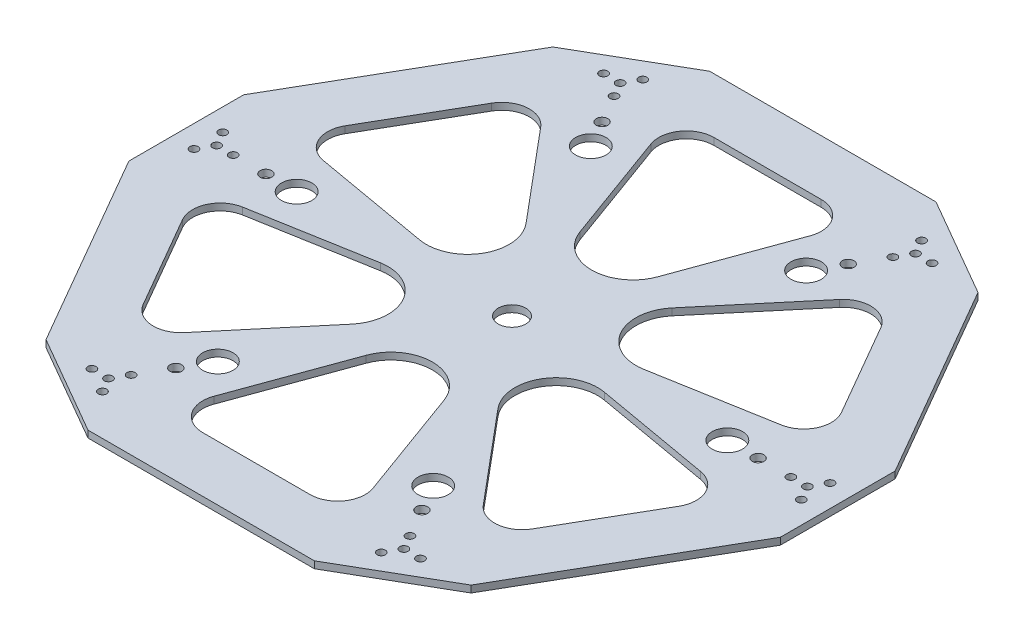
SolidWorks part; units mm, degrees
ref_plane "前视基准面" through (0, 0, 0) normal (0, 0, 1) x (1, 0, 0)
ref_plane "上视基准面" through (0, 0, 0) normal (0, 1, 0) x (1, 0, 0)
ref_plane "右视基准面" through (0, 0, 0) normal (1, 0, 0) x (0, 0, -1)
other "Configuration Table"
sketch "草图2" plane through (0, 0, 0) normal (0, 1, 0) x (1, 0, 0)
  line L1 (45, 0) -> (22.5, 38.9711)
  line L2 (22.5, 38.9711) -> (-22.5, 38.9711)
  line L3 (-22.5, 38.9711) -> (-45, 0)
  line L4 (-45, 0) -> (-22.5, -38.9711)
  line L5 (-22.5, -38.9711) -> (22.5, -38.9711)
  line L6 (22.5, -38.9711) -> (45, 0)
  line L7 (-54.5, 0) -> (-27.25, -47.1984)
  line L8 (-27.25, -47.1984) -> (27.25, -47.1984)
  line L9 (27.25, -47.1984) -> (54.5, 0)
  line L10 (54.5, 0) -> (27.25, 47.1984)
  line L11 (27.25, 47.1984) -> (-27.25, 47.1984)
  line L12 (-27.25, 47.1984) -> (-54.5, 0)
  circle A0 centre (0, 0) radius 38.9711 construction
  circle A1 centre (0, 0) radius 47.1984 construction
  circle A2 centre (0, 0) radius 5
  dimension "D3" = 10
  dimension "D1" = 45
  dimension "D2" = 9.5
extrude "凸台-拉伸1" add sketch "草图2" along normal blind 2.5 contours L5 L6 L1 L2 L3 L4 | L11 L12 L7 L8 L9 L10 L6 L5 L4 L3 L2 L1
sketch "草图3" plane through (0, 2.5, 0) normal (0, 1, 0) x (1, 0, 0)
  line L7 (-45, 0) -> (-22.5, -38.9711) construction
  line L8 (-22.5, -38.9711) -> (22.5, -38.9711) construction
  line L9 (22.5, -38.9711) -> (45, 0) construction
  line L10 (45, 0) -> (22.5, 38.9711) construction
  line L11 (22.5, 38.9711) -> (-22.5, 38.9711) construction
  line L12 (-22.5, 38.9711) -> (-45, 0) construction
  circle A0 centre (0, 0) radius 38.9711 construction
  circle A7 centre (-22.5, 38.9711) radius 2.1
  circle A8 centre (22.5, 38.9711) radius 2.1
  circle A9 centre (45, 0) radius 2.1
  circle A10 centre (22.5, -38.9711) radius 2.1
  circle A11 centre (-22.5, -38.9711) radius 2.1
  circle A12 centre (-45, 0) radius 2.1
  point P23 (0, 0)
  point P24 (0, 0)
  dimension "D2" = 4.2
  dimension "D1" = 45
  dimension "D3" = 6
extrude "切除-拉伸1" [suppressed] cut sketch "草图3" against normal blind 2.5
sketch "草图4" plane through (0, 2.5, 0) normal (0, 1, 0) x (1, 0, 0)
  line L0 (-27.25, 47.1984) -> (-54.5, 0) construction
  line L1 (-54.5, 0) -> (-27.25, -47.1984)
  line L2 (-27.25, -47.1984) -> (27.25, -47.1984)
  line L3 (27.25, -47.1984) -> (54.5, 0)
  line L4 (54.5, 0) -> (27.25, 47.1984)
  line L5 (27.25, 47.1984) -> (-27.25, 47.1984)
  line L6 (-27.25, 47.1984) -> (-54.5, 0)
  line L7 (-100.688, 0) -> (-50.344, -87.1984)
  line L8 (-50.344, -87.1984) -> (50.344, -87.1984)
  line L9 (50.344, -87.1984) -> (100.688, 0)
  line L10 (100.688, 0) -> (50.344, 87.1984)
  line L11 (50.344, 87.1984) -> (-50.344, 87.1984)
  line L12 (-50.344, 87.1984) -> (-100.688, 0)
  circle A0 centre (0, 0) radius 47.1984 construction
  circle A1 centre (0, 0) radius 87.1984 construction
  dimension "D1" = 40
extrude "凸台-拉伸2" add sketch "草图4" against normal up to surface (2.5 mm away) up to face at (0, 0, 5)
sketch "草图5" plane through (0, 2.5, 0) normal (0, 1, 0) x (1, 0, 0)
  line L0 (-50.344, 87.1984) -> (-100.688, 0) construction
  line L1 (-89.141, 0) -> (-44.5705, -77.1984) construction
  line L2 (-44.5705, -77.1984) -> (44.5705, -77.1984) construction
  line L3 (44.5705, -77.1984) -> (89.141, 0) construction
  line L4 (89.141, 0) -> (44.5705, 77.1984) construction
  line L5 (44.5705, 77.1984) -> (-44.5705, 77.1984) construction
  line L6 (-44.5705, 77.1984) -> (-89.141, 0) construction
  circle A0 centre (0, 0) radius 77.1984 construction
  circle A1 centre (-44.5705, 77.1984) radius 2.1
  circle A2 centre (44.5705, 77.1984) radius 2.1
  circle A3 centre (89.141, 0) radius 2.1
  circle A4 centre (44.5705, -77.1984) radius 2.1
  circle A5 centre (-44.5705, -77.1984) radius 2.1
  circle A6 centre (-89.141, 0) radius 2.1
  point P24 (0, 0)
  dimension "D2" = 4.2
  dimension "D1" = 10
  dimension "D3" = 6
extrude "切除-拉伸2" cut sketch "草图5" against normal blind 10
sketch "草图8" plane through (0, 2.5, 0) normal (0, 1, 0) x (1, 0, 0)
  line L0 (50.344, 87.1984) -> (-50.344, 87.1984) construction
  line L1 (-100.688, 0) -> (-50.344, -87.1984) construction
  circle A0 centre (-44.5705, 77.1984) radius 10
  circle A1 centre (44.5705, 77.1984) radius 10
  circle A2 centre (89.141, 0) radius 10
  circle A3 centre (44.5705, -77.1984) radius 10
  circle A4 centre (-44.5705, -77.1984) radius 10
  circle A5 centre (-89.141, 0) radius 10
  circle A6 centre (-113.6008, 65.5875) radius 60
  circle A7 centre (0, 131.175) radius 60
  circle A8 centre (113.6008, 65.5875) radius 60
  circle A9 centre (113.6008, -65.5875) radius 60
  circle A10 centre (0, -131.175) radius 60
  circle A11 centre (-113.6008, -65.5875) radius 60
  point P36 (0, 0)
  line M23 (-50.344, 87.1984) -> (-100.688, 0)
  line M24 (-100.688, 0) -> (-50.344, -87.1984)
  line M25 (-50.344, -87.1984) -> (50.344, -87.1984)
  line M26 (50.344, -87.1984) -> (100.688, 0)
  line M27 (100.688, 0) -> (50.344, 87.1984)
  line M28 (50.344, 87.1984) -> (-50.344, 87.1984)
  dimension "D1" = 120
  dimension "D2" = 6
extrude "切除-拉伸3" cut sketch "草图8" against normal blind 10 contours A0 M28 M23 | A7 A0 M28 | A6 A0 M23 | A7 M28 | A8 M27 | A9 M26 | A10 M25 | A11 M24 | A6 M23 | A1 M27 M28 | A7 A1 M28 | A8 A1 M27 | A8 A2 M27 | A2 M26 M27 | A9 A2 M26 | A9 A3 M26 | A10 A3 M25 | A3 M25 M26 | A11 A4 M24 | A4 M24 M25 | A10 A4 M25 | A5 M23 M24 | A6 A5 M23 | A11 A5 M24
sketch "草图10" plane through (0, 2.5, 0) normal (0, 1, 0) x (1, 0, 0)
  line L0 (-123, 12.1244) -> (-123, -12.1244)
  line L1 (-130, 0) -> (-65, -112.5833)
  line L2 (-65, -112.5833) -> (65, -112.5833)
  line L3 (65, -112.5833) -> (130, 0)
  line L4 (130, 0) -> (65, 112.5833)
  line L5 (65, 112.5833) -> (-65, 112.5833)
  line L6 (-65, 112.5833) -> (-130, 0)
  line L7 (-51, 112.5833) -> (-72, 100.4589)
  line L8 (72, 100.4589) -> (51, 112.5833)
  line L9 (123, -12.1244) -> (123, 12.1244)
  line L10 (51, -112.5833) -> (72, -100.4589)
  line L11 (-72, -100.4589) -> (-51, -112.5833)
  circle A0 centre (0, 0) radius 112.5833 construction
  arc A3 (-38.2033, 84.9093) -> (38.2033, 84.9093) centre (0, 131.175) ccw
  arc A5 (-38.2033, 84.9093) -> (38.2033, 84.9093) centre (0, 131.175) ccw
  arc A17 (-38.2033, 84.9093) -> (-54.432, 75.5397) centre (-44.5705, 77.1984) ccw
  arc A18 (-38.2033, 84.9093) -> (-54.432, 75.5397) centre (-44.5705, 77.1984) ccw
  arc A19 (-92.6353, 9.3696) -> (-54.432, 75.5397) centre (-113.6008, 65.5875) ccw
  arc A20 (-92.6353, 9.3696) -> (-54.432, 75.5397) centre (-113.6008, 65.5875) ccw
  arc A21 (-92.6353, 9.3696) -> (-92.6353, -9.3696) centre (-89.141, 0) ccw
  arc A22 (-92.6353, 9.3696) -> (-92.6353, -9.3696) centre (-89.141, 0) ccw
  arc A23 (-54.432, -75.5397) -> (-92.6353, -9.3696) centre (-113.6008, -65.5875) ccw
  arc A36 (-54.432, -75.5397) -> (-92.6353, -9.3696) centre (-113.6008, -65.5875) ccw
  arc A37 (-54.432, -75.5397) -> (-38.2033, -84.9093) centre (-44.5705, -77.1984) ccw
  arc A38 (-54.432, -75.5397) -> (-38.2033, -84.9093) centre (-44.5705, -77.1984) ccw
  arc A39 (38.2033, -84.9093) -> (-38.2033, -84.9093) centre (0, -131.175) ccw
  arc A40 (38.2033, -84.9093) -> (-38.2033, -84.9093) centre (0, -131.175) ccw
  arc A41 (38.2033, -84.9093) -> (54.432, -75.5397) centre (44.5705, -77.1984) ccw
  arc A42 (38.2033, -84.9093) -> (54.432, -75.5397) centre (44.5705, -77.1984) ccw
  arc A43 (92.6353, -9.3696) -> (54.432, -75.5397) centre (113.6008, -65.5875) ccw
  arc A44 (92.6353, -9.3696) -> (54.432, -75.5397) centre (113.6008, -65.5875) ccw
  arc A45 (92.6353, -9.3696) -> (92.6353, 9.3696) centre (89.141, 0) ccw
  arc A46 (92.6353, -9.3696) -> (92.6353, 9.3696) centre (89.141, 0) ccw
  arc A47 (54.432, 75.5397) -> (92.6353, 9.3696) centre (113.6008, 65.5875) ccw
  arc A48 (54.432, 75.5397) -> (92.6353, 9.3696) centre (113.6008, 65.5875) ccw
  arc A49 (54.432, 75.5397) -> (38.2033, 84.9093) centre (44.5705, 77.1984) ccw
  arc A50 (54.432, 75.5397) -> (38.2033, 84.9093) centre (44.5705, 77.1984) ccw
  point P47 (0, 0)
  arc M32 (38.2033, 84.9093) -> (-38.2033, 84.9093) centre (0, 131.175) cw
  arc M33 (-38.2033, 84.9093) -> (-54.432, 75.5397) centre (-44.5705, 77.1984) ccw
  arc M34 (-54.432, 75.5397) -> (-92.6353, 9.3696) centre (-113.6008, 65.5875) cw
  arc M35 (-92.6353, 9.3696) -> (-92.6353, -9.3696) centre (-89.141, 0) ccw
  arc M36 (-92.6353, -9.3696) -> (-54.432, -75.5397) centre (-113.6008, -65.5875) cw
  arc M37 (-54.432, -75.5397) -> (-38.2033, -84.9093) centre (-44.5705, -77.1984) ccw
  arc M38 (-38.2033, -84.9093) -> (38.2033, -84.9093) centre (0, -131.175) cw
  arc M39 (38.2033, -84.9093) -> (54.432, -75.5397) centre (44.5705, -77.1984) ccw
  arc M40 (54.432, -75.5397) -> (92.6353, -9.3696) centre (113.6008, -65.5875) cw
  arc M41 (92.6353, -9.3696) -> (92.6353, 9.3696) centre (89.141, 0) ccw
  arc M42 (92.6353, 9.3696) -> (54.432, 75.5397) centre (113.6008, 65.5875) cw
  arc M43 (54.432, 75.5397) -> (38.2033, 84.9093) centre (44.5705, 77.1984) ccw
  dimension "D2" = 130
  dimension "D3" = 7
  dimension "D1" = 0
  dimension "D4" = 6
extrude "凸台-拉伸3" add sketch "草图10" against normal up to surface (2.5 mm away) contours L1 L11 L2 L10 L3 L9 L4 L8 L5 L7 L6 L0 M32 M43 M42 M41 M40 M39 M38 M37 M36 M35 M34 M33 up to face at (-89.141, 0, 2.1)
sketch "草图11" plane through (0, 2.5, 0) normal (0, 1, 0) x (1, 0, 0)
  line L0 (-123, 12.1244) -> (-123, -12.1244) construction
  line L1 (-123, 0) -> (-107, 0) construction
  line L2 (-107, 0) -> (-101, 0) construction
  circle A0 centre (-107, 0) radius 1.5
  circle A1 centre (-101, 0) radius 1.5
  circle A2 centre (-110, -5.1962) radius 1.5
  circle A3 centre (-110, 5.1962) radius 1.5
  point P12 (-107, 0)
  dimension "D1" = 3
  dimension "D2" = 16
  dimension "D3" = 6
  dimension "D4" = 3
extrude "切除-拉伸4" cut sketch "草图11" against normal through all
pattern_circular "阵列(圆周)1" count 6 over 360 about axis through (0, 0, 0) along (0, 1, 0) of "切除-拉伸4"
sketch "草图12" plane through (0, 2.5, 0) normal (0, 1, 0) x (1, 0, 0)
  line L0 (0, 0) -> (60.8571, 0) construction
  line L1 (-118, 68.1273) -> (-118, -68.1273)
  line L2 (-118, -68.1273) -> (0, -136.2547)
  line L3 (0, -136.2547) -> (118, -68.1273)
  line L4 (118, -68.1273) -> (118, 68.1273)
  line L5 (118, 68.1273) -> (0, 136.2547)
  line L6 (0, 136.2547) -> (-118, 68.1273)
  line L7 (-51, 112.5833) -> (-72, 100.4589) construction
  line L9 (-145.896, 84.2331) -> (-145.896, -84.2331)
  line L10 (-145.896, -84.2331) -> (0, -168.4662)
  line L11 (0, -168.4662) -> (145.896, -84.2331)
  line L12 (145.896, -84.2331) -> (145.896, 84.2331)
  line L13 (145.896, 84.2331) -> (0, 168.4662)
  line L14 (0, 168.4662) -> (-145.896, 84.2331)
  circle A0 centre (0, 0) radius 118 construction
  circle A1 centre (0, 0) radius 145.896 construction
  line M51 (-123, -12.1244) -> (-72, -100.4589)
  line M52 (-72, -100.4589) -> (-51, -112.5833)
  line M53 (-51, -112.5833) -> (51, -112.5833)
  line M54 (51, -112.5833) -> (72, -100.4589)
  line M55 (72, -100.4589) -> (123, -12.1244)
  line M56 (123, -12.1244) -> (123, 12.1244)
  line M57 (123, 12.1244) -> (72, 100.4589)
  line M58 (72, 100.4589) -> (51, 112.5833)
  line M59 (51, 112.5833) -> (-51, 112.5833)
  line M60 (-51, 112.5833) -> (-72, 100.4589)
  line M61 (-72, 100.4589) -> (-123, 12.1244)
  line M62 (-123, 12.1244) -> (-123, -12.1244)
  dimension "D1" = 5
extrude "切除-拉伸12" cut sketch "草图12" against normal up to surface (2.5 mm away) contours L13 L14 L9 L10 L11 L12 L6 L5 L4 L3 L2 L1 M59 M58 M57 M56 M55 M54 M53 M52 M51 M62 M61 M60 | L3 M53 M54 M55 | L2 M51 M52 M53 | L1 M61 M62 M51 | L6 M59 M60 M61 | L5 M57 M58 M59 | L4 M55 M56 M57
sketch "草图13" plane through (0, 2.5, 0) normal (0, 1, 0) x (1, 0, 0)
  circle A0 centre (-78, 0) radius 5.5
  circle A2 centre (-39, 67.55) radius 5.5
  circle A3 centre (39, 67.55) radius 5.5
  circle A4 centre (78, 0) radius 5.5
  circle A5 centre (39, -67.55) radius 5.5
  circle A6 centre (-39, -67.55) radius 5.5
  point P16 (0, 0)
  dimension "D1" = 11
  dimension "D2" = 78
  dimension "D3" = 6
extrude "切除-拉伸13" cut sketch "草图13" against normal blind 10
sketch "草图14" plane through (0, 2.5, 0) normal (0, 1, 0) x (1, 0, 0)
  line L0 (-41, 112.5833) -> (0, 0)
  line L1 (0, 0) -> (41, 112.5833)
  line L2 (41, 112.5833) -> (-41, 112.5833)
  line L3 (-33.7165, 92.5833) -> (33.7165, 92.5833)
  line L4 (0, 112.5833) -> (0, 0) construction
  circle A0 centre (0, 43.8353) radius 15
  circle A1 centre (-19.4323, 82.5833) radius 10
  circle A2 centre (19.4323, 82.5833) radius 10
  dimension "D1" = 30
  dimension "D3" = 20
  dimension "D4" = 20
  dimension "D2" = 20
extrude "切除-拉伸14" cut sketch "草图14" against normal blind 10 contours A2 | L3 L4 A0 L1 A2 | L4 L3 A1 L0 A0 | A1 | L4 A0 | A0 L4
pattern_circular "阵列(圆周)2" count 6 over 360 about axis through (0, 0, 0) along (0, 1, 0) of "切除-拉伸14"
sketch "草图15" plane through (0, 2.5, 0) normal (0, 1, 0) x (1, 0, 0)
  line L0 (-118, 0) -> (118, 0) construction
  line L1 (-118, 20.7846) -> (-118, -20.7846) construction
  line L2 (118, -20.7846) -> (118, 20.7846) construction
  line L3 (-59, 102.191) -> (59, -102.191) construction
  line L4 (-41, 112.5833) -> (-77, 91.7987) construction
  line L5 (41, -112.5833) -> (77, -91.7987) construction
